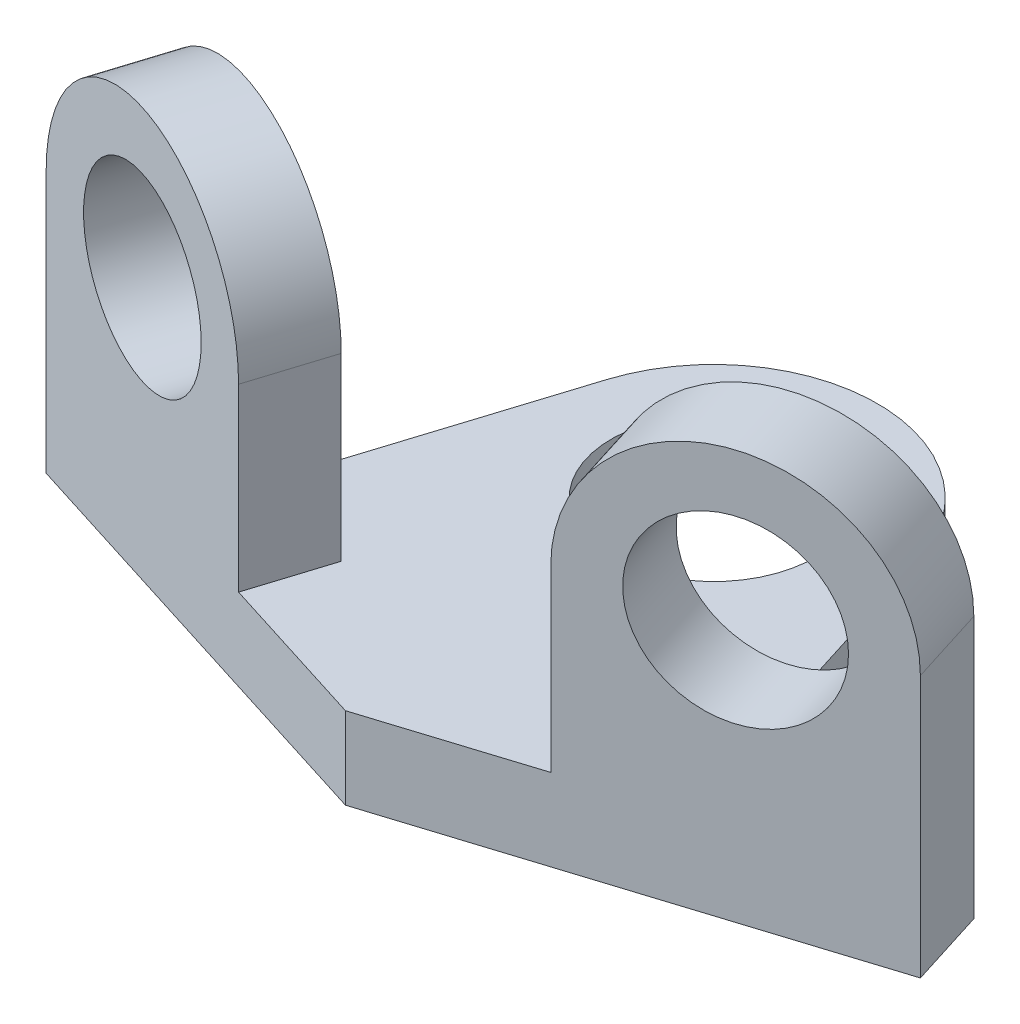
SolidWorks part; units mm, degrees
ref_plane "Front Plane" through (0, 0, 0) normal (0, 0, 1) x (1, 0, 0)
ref_plane "Top Plane" through (0, 0, 0) normal (0, 1, 0) x (1, 0, 0)
ref_plane "Right Plane" through (0, 0, 0) normal (1, 0, 0) x (0, 0, -1)
sketch "Sketch1" plane through (0, 0, 0) normal (0, 1, 0) x (1, 0, 0)
  line L0 (0, 0) -> (0, 73.4547) construction
  line L1 (0, 0) -> (31.9798, 10.0832)
  line L2 (31.9798, 10.0832) -> (19.0743, 51.0141)
  line L3 (-19.0743, 51.0141) -> (-31.9798, 10.0832)
  line L4 (-31.9798, 10.0832) -> (0, 0)
  arc A0 (19.0743, 51.0141) -> (-19.0743, 51.0141) centre (0, 45) ccw
  circle A1 centre (0, 45) radius 12.5
  point P7 (0, 73.4547)
  dimension "D1" = 20
  dimension "D4" = 25
  dimension "D2" = 35
  dimension "D3" = 45
extrude "Boss-Extrude1" add sketch "Sketch1" along normal mid plane 10
sketch "Sketch2" plane through (0, 0, 0) normal (0.3007, 0, 0.9537) x (0.9537, 0, -0.3007)
  line L0 (20, -5) -> (20, 27)
  line L1 (0, -5) -> (33.5318, -5) construction
  line L2 (56, 27) -> (56, -5)
  line L3 (56, -5) -> (20, -5)
  line L4 (0, 5) -> (0, -5) construction
  arc A0 (20, 27) -> (56, 27) centre (38, 27) cw
  circle A1 centre (38, 27) radius 11
  dimension "D3" = 32
  dimension "D4" = 22
  dimension "D1" = 36
  dimension "D2" = 20
extrude "Boss-Extrude2" add sketch "Sketch2" against normal blind 10
mirror "Mirror2" about plane through (0, 0, 0) normal (1, 0, 0) of "Boss-Extrude2"
